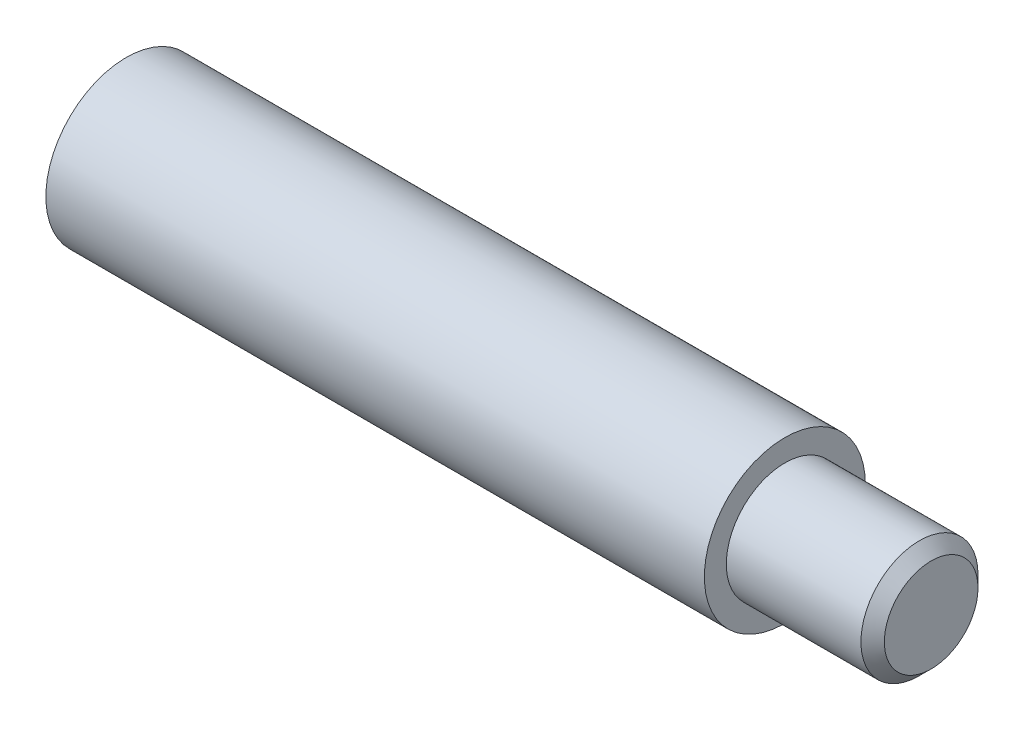
SolidWorks part; units mm, degrees
material "Plain Carbon Steel"
ref_plane "Front Plane" through (0, 0, 0) normal (0, 0, 1) x (1, 0, 0)
ref_plane "Top Plane" through (0, 0, 0) normal (0, 1, 0) x (1, 0, 0)
ref_plane "Right Plane" through (0, 0, 0) normal (1, 0, 0) x (0, 0, -1)
sketch "Sketch1" plane through (0, 0, 0) normal (0, 0, 1) x (1, 0, 0)
  line L0 (-15.5, 2.4585) -> (-14.0228, 0)
  line L1 (-14.0228, 0) -> (27.5, 0)
  line L2 (27.5, 0) -> (27.5, 3.2)
  line L3 (27.5, 3.2) -> (26.7, 4)
  line L4 (26.7, 4) -> (17.5, 4)
  line L5 (17.5, 4) -> (17.5, 5.5)
  line L6 (17.5, 5.5) -> (-27.5, 5.5)
  line L7 (-27.5, 5.5) -> (-27.5, 3.2585)
  line L8 (-27.5, 3.2585) -> (-26.7, 2.4585)
  line L9 (-26.7, 2.4585) -> (-15.5, 2.4585)
  line L10 (-27.5, 0) -> (27.5, 0) construction
  dimension "D1" = 41.5228
  dimension "D2" = 45
  dimension "D3" = 9.2
  dimension "D4" = 10
  dimension "D5" = 11.2
  dimension "D6" = 2.2415
  dimension "D7" = 5.5
  dimension "D8" = 4
  dimension "D9" = 3.0415
revolve "Revolve1" add sketch "Sketch1" angle 360 about L10
cosmetic thread "Cosmetic Thread1" parameters "D1"=10, "D2"=6.891
cosmetic thread "Cosmetic Thread2" parameters "D1"=11, "D2"=6
